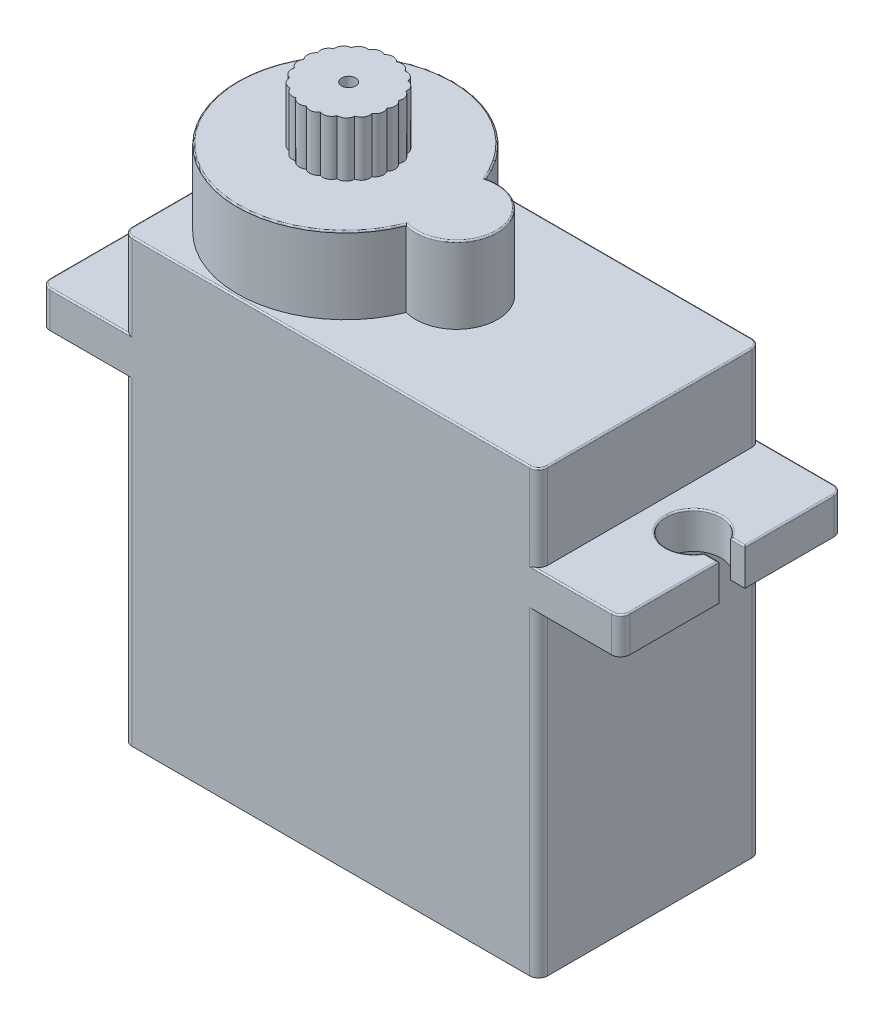
SolidWorks part; units mm, degrees
ref_plane "前视基准面" through (0, 0, 0) normal (0, 0, 1) x (1, 0, 0)
ref_plane "上视基准面" through (0, 0, 0) normal (0, 1, 0) x (1, 0, 0)
ref_plane "右视基准面" through (0, 0, 0) normal (1, 0, 0) x (0, 0, -1)
sketch "草图1" plane through (0, 0, 0) normal (0, 0, 1) x (1, 0, 0)
  line L1 (-11.4, 12.1) -> (11.4, 12.1)
  line L2 (-11.4, 12.1) -> (-11.4, -12.1)
  line L3 (-11.4, -12.1) -> (11.4, -12.1)
  line L4 (11.4, 12.1) -> (11.4, -12.1)
  line L5 (-11.4, 12.1) -> (11.4, -12.1) construction
  line L6 (-11.4, -12.1) -> (11.4, 12.1) construction
  point P0 (0, 0)
  dimension "D1" = 22.8
  dimension "D2" = 24.2
extrude "凸台-拉伸1" add sketch "草图1" along normal mid plane 12.2
ref_plane "基准面1" through (0, 12.1, 0) normal (0, 1, 0) x (1, 0, 0)
sketch "草图4" plane through (0, 12.1, 0) normal (0, 1, 0) x (1, 0, 0)
  line L1 (12.5177, 0) -> (-12.5177, 0) construction
  line L2 (-11.4, -6.1) -> (-11.4, 6.1) construction
  arc A1 (0.2098, 2.1712) -> (0.2098, -2.1712) centre (-5.3, 0) ccw
  arc A3 (0.2098, -2.1712) -> (0.2098, 2.1712) centre (0.8, 0) ccw
  point P0 (-5.3, 0)
  point P6 (0, 0)
  dimension "D1" = 6.1
  dimension "D2" = 4.5
extrude "凸台-拉伸3" add sketch "草图4" along normal blind 4.2
ref_plane "基准面2" through (0, 0, 6.1) normal (0, 0, 1) x (1, 0, 0)
sketch "草图5" plane through (0, 0, 6.1) normal (0, 0, 1) x (1, 0, 0)
  line L0 (0, 15.0905) -> (0, -15.0905) construction
  line L1 (11.4, -12.1) -> (11.4, 12.1) construction
  line L2 (11.4, 7.4) -> (15.9, 7.4)
  line L3 (11.4, 7.4) -> (11.4, 5.4)
  line L4 (11.4, 5.4) -> (15.9, 5.4)
  line L5 (15.9, 7.4) -> (15.9, 5.4)
  line L6 (-11.4, -12.1) -> (11.4, -12.1) construction
  line L7 (-15.9, 7.4) -> (-15.9, 5.4)
  line L8 (-11.4, 5.4) -> (-15.9, 5.4)
  line L9 (-11.4, 7.4) -> (-11.4, 5.4)
  line L10 (-11.4, 7.4) -> (-15.9, 7.4)
  point P4 (0, 0)
  dimension "D1" = 4.5
  dimension "D2" = 2
  dimension "D3" = 17.5
extrude "凸台-拉伸4" add sketch "草图5" against normal blind 12.2
ref_plane "基准面3" through (0, 7.4, 0) normal (0, 1, 0) x (1, 0, 0)
sketch "草图6" plane through (0, 7.4, 0) normal (0, 1, 0) x (1, 0, 0)
  line L0 (-19.3337, 0) -> (19.3337, 0) construction
  line L1 (15.9, 0.7157) -> (15.1183, 0.7157)
  line L2 (15.9, 6.1) -> (15.9, -6.1) construction
  line L3 (15.9, -0.7157) -> (15.1183, -0.7157)
  line L4 (0, -12.1111) -> (0, 12.1111) construction
  line L5 (-15.9, 0.7157) -> (-15.1183, 0.7157)
  line L6 (-15.9, -0.7157) -> (-15.1183, -0.7157)
  line L7 (-15.9, 0.7157) -> (-15.9, -0.7157)
  line L8 (15.9, 0.7157) -> (15.9, -0.7157)
  line L9 (15.9, -6.1) -> (11.4, -6.1) construction
  line L10 (11.4, -6.1) -> (11.4, 6.1) construction
  arc A0 (15.1183, 0.7157) -> (15.1183, -0.7157) centre (13.8, 0) ccw
  arc A1 (-15.1183, 0.7157) -> (-15.1183, -0.7157) centre (-13.8, 0) cw
  point P4 (0, 0)
  point P15 (0, 0)
  dimension "D1" = 3
  dimension "D2" = 13.8
  dimension "D3" = 6.1
  dimension "D4" = 2.4
extrude "切除-拉伸1" cut sketch "草图6" against normal blind 2
ref_plane "基准面4" through (0, 16.3, 0) normal (0, 1, 0) x (1, 0, 0)
sketch "草图7" plane through (0, 16.3, 0) normal (0, 1, 0) x (1, 0, 0)
  circle A0 centre (-5.1222, 0) radius 2.25
  arc A1 (0.2098, 2.1712) -> (0.2098, -2.1712) centre (-5.3, 0) ccw construction
  arc A2 (-4.2317, 2.0663) -> (-3.5118, 1.5713) centre (-5.1222, 0) cw
  arc A3 (-4.1049, 2.0662) -> (-3.5411, 1.6745) centre (-4.0073, 1.6051) cw
  arc A4 (-3.6622, 1.712) -> (-3.1202, 1.0268) centre (-5.1222, 0) cw
  arc A5 (-3.5411, 1.6745) -> (-3.1178, 1.1341) centre (-3.5837, 1.2052) cw
  arc A6 (-3.2225, 1.2056) -> (-2.9065, 0.3911) centre (-5.1222, 0) cw
  arc A7 (-3.1178, 1.1341) -> (-2.8726, 0.4929) centre (-3.2968, 0.6981) cw
  arc A8 (-2.9515, 0.5921) -> (-2.8896, -0.2794) centre (-5.1222, 0) cw
  arc A9 (-2.8726, 0.4929) -> (-2.8272, -0.1921) centre (-3.1721, 0.1291) cw
  arc A10 (-2.8734, -0.074) -> (-3.0712, -0.925) centre (-5.1222, 0) cw
  arc A11 (-2.8272, -0.1921) -> (-2.9858, -0.86) centre (-3.2207, -0.4514) cw
  arc A12 (-2.9951, -0.7336) -> (-3.4349, -1.4885) centre (-5.1222, 0) cw
  arc A13 (-2.9858, -0.86) -> (-3.3342, -1.4515) centre (-3.4383, -0.9919) cw
  arc A14 (-3.3059, -1.3279) -> (-3.9486, -1.9197) centre (-5.1222, 0) cw
  arc A15 (-3.3342, -1.4515) -> (-3.8415, -1.914) centre (-3.8054, -1.4441) cw
  arc A16 (-3.778, -1.8043) -> (-4.5666, -2.1803) centre (-5.1222, 0) cw
  arc A17 (-3.8415, -1.914) -> (-4.4626, -2.2065) centre (-4.2896, -1.7681) cw
  arc A18 (-4.3695, -2.1204) -> (-5.234, -2.2472) centre (-5.1222, 0) cw
  arc A19 (-4.4626, -2.2065) -> (-5.1422, -2.3029) centre (-4.8478, -1.935) cw
  arc A20 (-5.028, -2.248) -> (-5.8914, -2.1144) centre (-5.1222, 0) cw
  arc A21 (-5.1422, -2.3029) -> (-5.8202, -2.1947) centre (-5.4303, -1.9299) cw
  arc A22 (-5.6948, -2.1759) -> (-6.4805, -1.7938) centre (-5.1222, 0) cw
  arc A23 (-5.8202, -2.1947) -> (-6.436, -1.8915) centre (-5.9854, -1.7533) cw
  arc A24 (-6.3107, -1.9105) -> (-6.9488, -1.3137) centre (-5.1222, 0) cw
  arc A25 (-6.436, -1.8915) -> (-6.9352, -1.4202) centre (-6.4639, -1.421) cw
  arc A26 (-6.821, -1.4753) -> (-7.2549, -0.717) centre (-5.1222, 0) cw
  arc A27 (-6.9352, -1.4202) -> (-7.2733, -0.8227) centre (-6.8231, -0.9624) cw
  arc A28 (-7.1804, -0.909) -> (-7.3715, -0.0565) centre (-5.1222, 0) cw
  arc A29 (-7.2733, -0.8227) -> (-7.4202, -0.1521) centre (-7.0312, -0.4183) cw
  arc A30 (-7.3569, -0.262) -> (-7.2882, 0.609) centre (-5.1222, 0) cw
  arc A31 (-7.4202, -0.1521) -> (-7.3629, 0.532) centre (-7.0697, 0.163) cw
  arc A32 (-7.3348, 0.4084) -> (-7.0125, 1.2204) centre (-5.1222, 0) cw
  arc A33 (-7.3629, 0.532) -> (-7.1066, 1.1688) centre (-6.9352, 0.7298) cw
  arc A34 (-7.1162, 1.0424) -> (-6.5688, 1.7234) centre (-5.1222, 0) cw
  arc A35 (-7.1066, 1.1688) -> (-6.6739, 1.7018) centre (-6.6395, 1.2318) cw
  arc A36 (-6.7203, 1.5838) -> (-5.9965, 2.0732) centre (-5.1222, 0) cw
  arc A37 (-6.6739, 1.7018) -> (-6.1033, 2.0836) centre (-6.209, 1.6243) cw
  arc A38 (-6.1825, 1.9845) -> (-5.3466, 2.2388) centre (-5.1222, 0) cw
  arc A39 (-6.1033, 2.0836) -> (-5.4456, 2.2802) centre (-5.682, 1.8724) cw
  arc A40 (-5.5504, 2.2089) -> (-4.6767, 2.2055) centre (-5.1222, 0) cw
  arc A41 (-5.4456, 2.2802) -> (-4.7592, 2.2742) centre (-5.1052, 1.9543) cw
  arc A42 (-4.8803, 2.237) -> (-4.0465, 1.9762) centre (-5.1222, 0) cw
  arc A43 (-4.7592, 2.2742) -> (-4.1049, 2.0662) centre (-4.5299, 1.8624) cw
  circle A44 centre (-5.1222, 0) radius 0.3845
  point P5 (-11.2222, 0)
  point P72 (-5.1222, 0)
  dimension "D1" = 6.1
  dimension "D2" = 4.5
  dimension "D4" = 0.4713
  dimension "D6" = 0.7689
  dimension "D5" = 0.8737
  dimension "D3" = 21
extrude "凸台-拉伸5" add sketch "草图7" along normal blind 3 contours A35 A0 | A33 A0 | A31 A0 | A29 A0 | A0 | A27 A0 | A25 A0 | A23 A0 | A21 A0 | A41 A0 | A37 A0 | A39 A0 | A43 A0 | A3 A0 | A5 A0 | A7 A0 | A9 A0 | A11 A0 | A13 A0 | A15 A0 | A17 A0 | A19 A0
fillet "圆角1" radius 0.5 12 edges at (15.9, 6.4, -6.1) (15.9, 6.4, 6.1) (-15.9, 6.4, 6.1) (-15.9, 6.4, -6.1) (-11.4, -3.35, -6.1) (-11.4, -3.35, 6.1) (-11.4, 9.75, -6.1) (-11.4, 9.75, 6.1) (11.4, -3.35, -6.1) (11.4, -3.35, 6.1) (11.4, 9.75, -6.1) (11.4, 9.75, 6.1)
fillet "圆角2" radius 0.08 27 edges at (3.05, 16.3, 0) (-11.2222, 16.3, 0) (-11.2536, 12.1, 5.9536) (15.5091, 7.4, 0.7157) (15.5091, 7.4, -0.7157) (12.3, 7.4, 0) (13.15, 7.4, 6.1) (15.7536, 7.4, 5.9536) (15.9, 7.4, 3.1578) (15.9, 7.4, -3.1578) (15.7536, 7.4, -5.9536) (13.15, 7.4, -6.1) (-15.5091, 7.4, 0.7157) (-12.3, 7.4, 0) (-15.9, 7.4, -3.1578) (-15.7536, 7.4, -5.9536) (-13.15, 7.4, -6.1) (-15.9, 7.4, 3.1578) (-15.7536, 7.4, 5.9536) (-13.15, 7.4, 6.1) (-11.4, 12.1, 0) (-11.2536, 12.1, -5.9536) (11.2536, 12.1, 5.9536) (11.2536, 12.1, -5.9536) (0, 12.1, -6.1) (11.4, 12.1, 0) (0, 12.1, 6.1)
